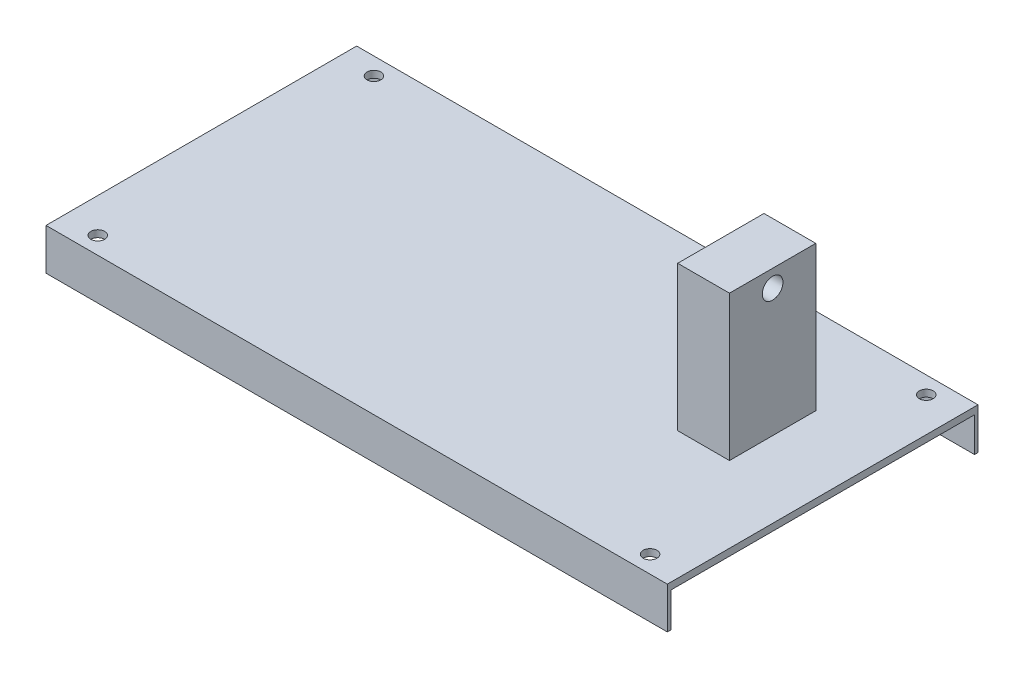
SolidWorks part; units mm, degrees
material "Hexcel AS4C (3000 Filaments)"
ref_plane "Ön Düzlem" through (0, 0, 0) normal (0, 0, 1) x (1, 0, 0)
ref_plane "Üst Düzlem" through (0, 0, 0) normal (0, 1, 0) x (1, 0, 0)
ref_plane "Sağ Düzlem" through (0, 0, 0) normal (1, 0, 0) x (0, 0, -1)
sketch "Çizim1" plane through (0, 0, 0) normal (0, 1, 0) x (1, 0, 0)
  line L1 (-90, 45) -> (90, 45)
  line L2 (-90, 45) -> (-90, -45)
  line L3 (-90, -45) -> (90, -45)
  line L4 (90, 45) -> (90, -45)
  line L5 (-90, 45) -> (90, -45) construction
  line L6 (-90, -45) -> (90, 45) construction
  point P0 (0, 0)
  dimension "D1" = 180
  dimension "D2" = 90
extrude "Yükseklik-Ekstrüzyon1" add sketch "Çizim1" along normal blind 2
sketch "Çizim2" plane through (0, 0, 0) normal (0, -1, 0) x (1, 0, 0)
  line L0 (90, 45) -> (90, -45) construction
  line L1 (-90, 45) -> (90, 45)
  line L2 (-90, 45) -> (-90, 44)
  line L3 (-90, 44) -> (90, 44)
  line L4 (90, 45) -> (90, 44)
  dimension "D1" = 1
extrude "Yükseklik-Ekstrüzyon2" add sketch "Çizim2" along normal blind 10
mirror "Aynalama1" about plane through (0, 0, 0) normal (0, 0, 1) of "Yükseklik-Ekstrüzyon2"
sketch "Çizim3" plane through (0, 0, 0) normal (0, -1, 0) x (1, 0, 0)
  line L1 (-90, -44) -> (-90, 44) construction
  circle A0 centre (-80, 40) radius 2
  circle A1 centre (-80, -40) radius 2
  dimension "D1" = 4
  dimension "D2" = 80
  dimension "D3" = 40
  dimension "D4" = 10
extrude "Kes-Ekstrüzyon1" cut sketch "Çizim3" against normal blind 10
mirror "Aynalama2" about plane through (0, 0, 0) normal (1, 0, 0) of "Kes-Ekstrüzyon1"
sketch "Çizim6" plane through (0, 2, 0) normal (0, 1, 0) x (1, 0, 0)
  line L1 (53, 20) -> (68, 20)
  line L2 (53, 20) -> (53, -5)
  line L3 (53, -5) -> (68, -5)
  line L4 (68, 20) -> (68, -5)
  line L5 (90, 45) -> (-90, 45) construction
  dimension "D1" = 25
  dimension "D2" = 15
  dimension "D3" = 53
  dimension "D4" = 25
extrude "Yükseklik-Ekstrüzyon3" add sketch "Çizim6" along normal blind 42
sketch "Çizim7" plane through (53, 0, 0) normal (-1, 0, 0) x (0, 0, 1)
  line L0 (5, 44) -> (5, 2) construction
  line L1 (-20, 44) -> (5, 44) construction
  circle A0 centre (-7.5, 39) radius 3
  dimension "D1" = 6
  dimension "D2" = 12.5
  dimension "D3" = 5
extrude "Kes-Ekstrüzyon2" cut sketch "Çizim7" against normal blind 49
